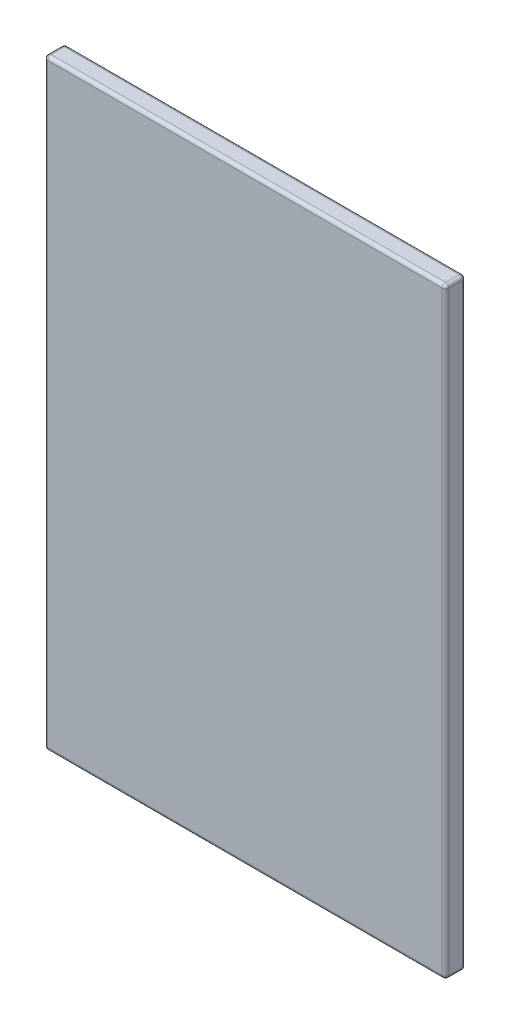
SolidWorks part; units mm, degrees
ref_plane "前视基准面" through (0, 0, 0) normal (0, 0, 1) x (1, 0, 0)
ref_plane "上视基准面" through (0, 0, 0) normal (0, 1, 0) x (1, 0, 0)
ref_plane "右视基准面" through (0, 0, 0) normal (1, 0, 0) x (0, 0, -1)
sketch "草图1" plane through (0, 0, 0) normal (0, 0, 1) x (1, 0, 0)
  line L0 (-43.2882, 0) -> (52.6002, 0) construction
  line L1 (-30, 45) -> (30, 45)
  line L2 (-30, 45) -> (-30, -45)
  line L3 (-30, -45) -> (30, -45)
  line L4 (30, 45) -> (30, -45)
  line L5 (0, 58.7663) -> (0, -46.6858) construction
  dimension "D1" = 60
  dimension "D2" = 90
extrude "凸台-拉伸1" add sketch "草图1" along normal blind 3
fillet "圆角1" radius 0.5 12 edges at (-30, 0, 0) (30, 0, 0) (30, -45, 1.5) (0, -45, 0) (0, -45, 3) (-30, -45, 1.5) (0, 45, 0) (-30, 45, 1.5) (30, 45, 1.5) (30, 0, 3) (-30, 0, 3) (0, 45, 3)
